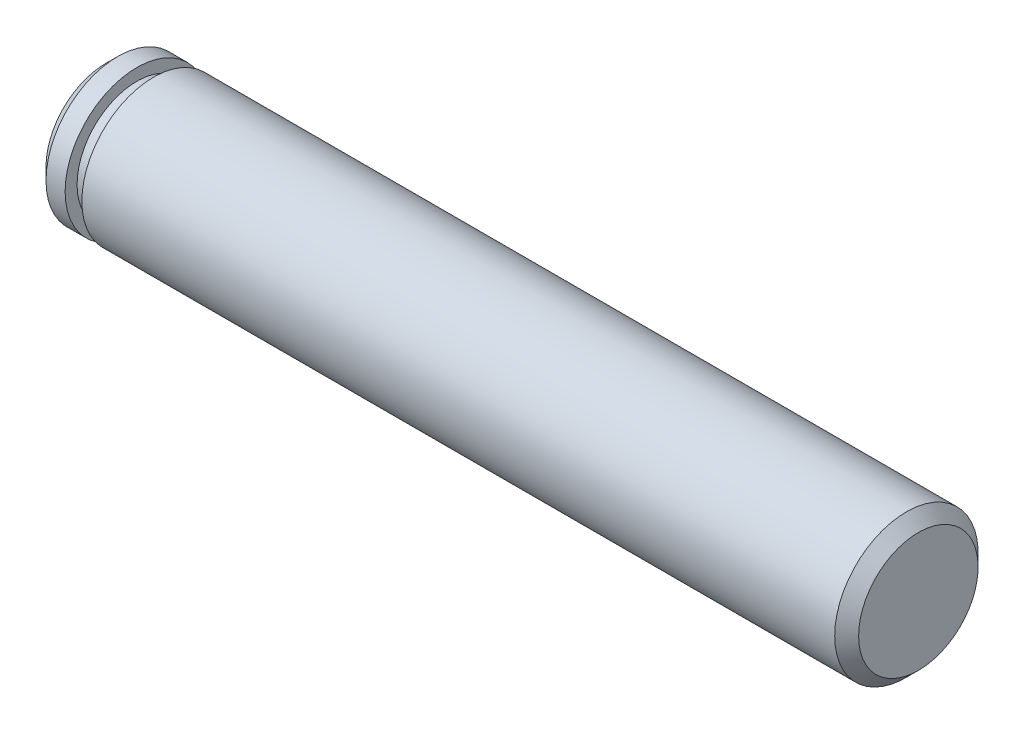
SolidWorks part; units mm, degrees
ref_plane "Front Plane" through (0, 0, 0) normal (0, 0, 1) x (1, 0, 0)
ref_plane "Top Plane" through (0, 0, 0) normal (0, 1, 0) x (1, 0, 0)
ref_plane "Right Plane" through (0, 0, 0) normal (1, 0, 0) x (0, 0, -1)
ref_plane "Plane1" through (0, 0, 0) normal (0, 0, 1) x (1, 0, 0)
sketch "Sketch1" plane through (0, 0, 0) normal (0, 0, 1) x (1, 0, 0)
  line L0 (0, 0) -> (0, 3)
  line L1 (0, 3) -> (31.5, 3)
  line L2 (31.5, 3) -> (32, 2.5)
  line L3 (32, 2.5) -> (32, 0)
  line L4 (32, 0) -> (0, 0)
  line L5 (32, 0) -> (0, 0) construction
revolve "Revolve1" add sketch "Sketch1" angle 360 about L5
ref_plane "Plane2" through (0, 0, 0) normal (0, 0, 1) x (1, 0, 0)
sketch "Sketch2" plane through (0, 0, 0) normal (0, 0, 1) x (1, 0, 0)
  line L0 (-2, 0) -> (-2, 2.5)
  line L1 (-2, 2.5) -> (-1.5, 3)
  line L2 (-1.5, 3) -> (-0.7, 3)
  line L3 (-0.7, 3) -> (-0.7, 2.5)
  line L4 (-0.7, 2.5) -> (0, 2.5)
  line L5 (0, 2.5) -> (0, 0)
  line L6 (0, 0) -> (-2, 0)
  line L7 (0, 0) -> (-2, 0) construction
revolve "Revolve2" add sketch "Sketch2" angle 360 about L7
